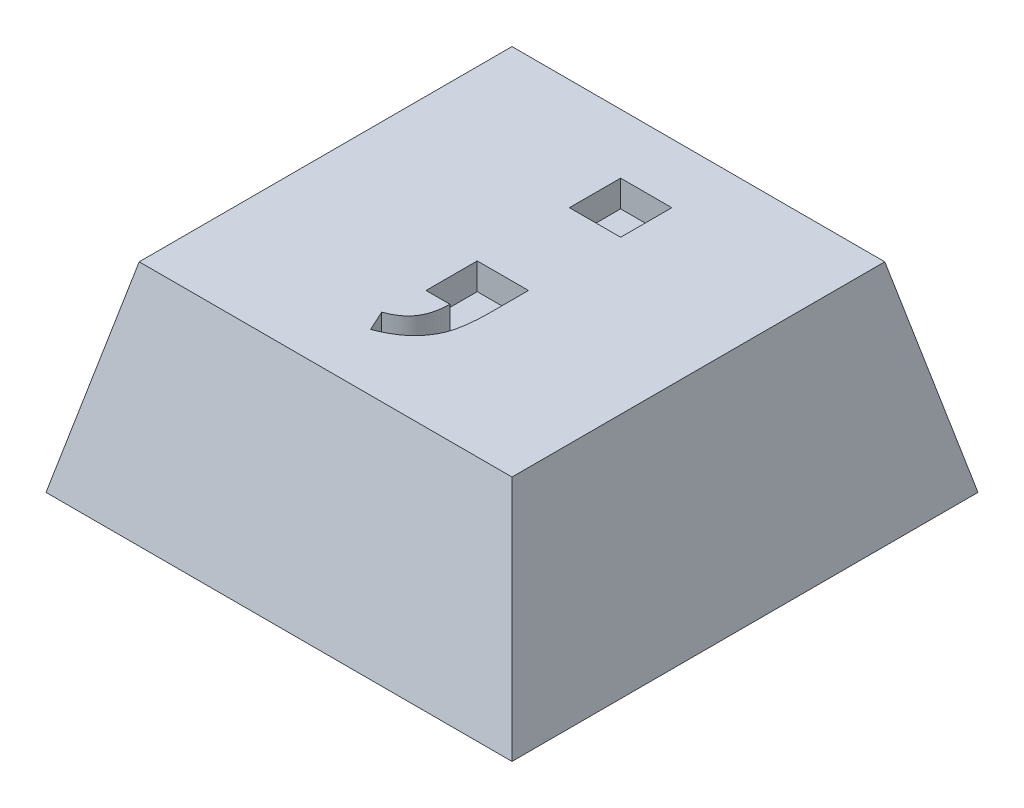
SolidWorks part; units mm, degrees
ref_plane "Front Plane" through (0, 0, 0) normal (0, 0, 1) x (1, 0, 0)
ref_plane "Top Plane" through (0, 0, 0) normal (0, 1, 0) x (1, 0, 0)
ref_plane "Right Plane" through (0, 0, 0) normal (1, 0, 0) x (0, 0, -1)
sketch "Sketch1" plane through (0, 0, 0) normal (0, 1, 0) x (1, 0, 0)
  line L1 (0, 0) -> (7, 0)
  line L2 (0, 0) -> (0, 7)
  line L3 (0, 7) -> (7, 7)
  line L4 (7, 0) -> (7, 7)
  dimension "D1" = 7
  dimension "D2" = 7
extrude "Boss-Extrude1" add sketch "Sketch1" along normal blind 3
sketch "Sketch2" plane through (0, 0, 0) normal (0, 0, 1) x (1, 0, 0)
  line L0 (0, 0) -> (0.7, 3)
  line L1 (0, 3) -> (7, 3) construction
  line L2 (0.7, 3) -> (0, 3)
  line L3 (0, 3) -> (0, 0)
  line L4 (7, 0) -> (6.3, 3)
  line L5 (6.3, 3) -> (7, 3)
  line L6 (7, 3) -> (7, 0)
  dimension "D1" = 0.7
  dimension "D2" = 0.7
extrude "Cut-Extrude1" cut sketch "Sketch2" against normal blind 7
sketch "Sketch3" plane through (0, 0, 0) normal (1, 0, 0) x (0, 0, -1)
  line L0 (0, 0) -> (0.7, 3)
  line L1 (7, 3) -> (0, 3) construction
  line L2 (0.7, 3) -> (0, 3)
  line L3 (0, 3) -> (0, 0)
  line L4 (7, 3) -> (6.3, 3)
  line L5 (6.3, 3) -> (7, 0)
  line L6 (7, 3) -> (7, 0)
  dimension "D1" = 0.7
  dimension "D2" = 0.7
extrude "Cut-Extrude2" cut sketch "Sketch3" along normal blind 11
sketch "Sketch4" plane through (0, 0, 0) normal (0, -1, 0) x (1, 0, 0)
  line L0 (3.5, 0) -> (3.5, -7) construction
  line L1 (0, 0) -> (7, 0) construction
  line L2 (7, -7) -> (0, -7) construction
  line L3 (0, -3.5) -> (7, -3.5) construction
  line L4 (0, -7) -> (0, 0) construction
  line L5 (7, 0) -> (7, -7) construction
  circle A0 centre (3.5, -3.5) radius 1.8
  dimension "D1" = 3.6
extrude "Cut-Extrude3" cut sketch "Sketch4" against normal blind 0.8
sketch "Sketch5" plane through (0, 3, 0) normal (0, 1, 0) x (1, 0, 0)
  text T0 ";" font "Arial" height 4
extrude "Cut-Extrude4" cut sketch "Sketch5" against normal blind 0.4
